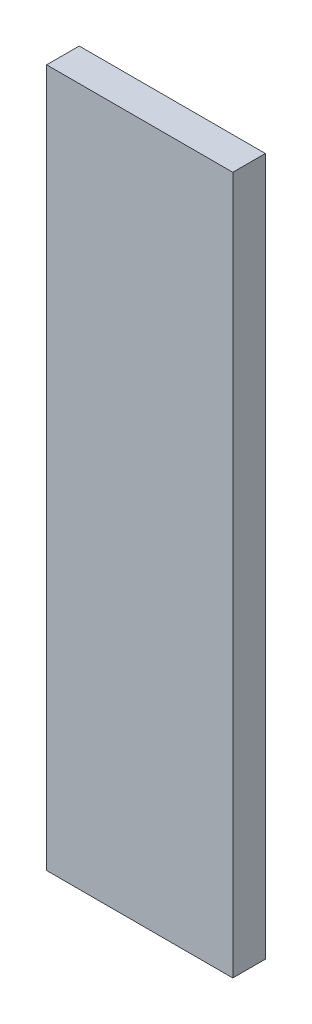
SolidWorks part; units mm, degrees
material "Brass"
ref_plane "Front Plane" through (0, 0, 0) normal (0, 0, 1) x (1, 0, 0)
ref_plane "Top Plane" through (0, 0, 0) normal (0, 1, 0) x (1, 0, 0)
ref_plane "Right Plane" through (0, 0, 0) normal (1, 0, 0) x (0, 0, -1)
sketch "Sketch1" plane through (0, 0, 0) normal (0, 0, 1) x (1, 0, 0)
  line L0 (-18.1394, 68.0022) -> (18.1394, -68.0022) construction
  line L1 (-18.1394, 68.0022) -> (18.1394, 68.0022)
  line L2 (-18.1394, 68.0022) -> (-18.1394, -68.0022)
  line L3 (-18.1394, -68.0022) -> (18.1394, -68.0022)
  line L4 (18.1394, 68.0022) -> (18.1394, -68.0022)
  dimension "D1" = 36.2788
  dimension "D2" = 136.0043
extrude "Extrude1" add sketch "Sketch1" along normal blind 6.35
hole_wizard "#3-48 Tapped Hole1" positions "Sketch2" profile "Sketch3" tap size "#3-48" standard "Ansi Inch"
sketch "Sketch2" plane through (-14.071, -68.0022, 88.9006) normal (0, -1, 0) x (0, 0, -1)
  point P0 (85.7256, 25.8604)
  point P1 (85.7256, 0.8922)
sketch "Sketch3" plane through (11.7894, -68.0022, 3.175) normal (1, 0, 0) x (0, 0, -1)
  line L0 (0, 0) -> (0, 9.743)
  line L1 (0, 9.743) -> (0.9969, 9.144)
  line L2 (0.9969, 9.144) -> (0.997, 7.62)
  line L3 (0.997, 7.62) -> (1.2573, 7.62)
  line L4 (1.2573, 7.62) -> (1.2573, 0)
  line L5 (1.2573, 0) -> (0, 0)
  line L10 (0, 9.743) -> (-0.997, 9.144) construction
  line L11 (0, -6.35) -> (0, 107.95) construction
  dimension "Tap Drill Dia." = 1.9939
  dimension "Tap Drill Depth" = 9.144
  dimension "Thread Major Dia." = 2.5146
  dimension "Drill Angle" = 118
  dimension "Thread Depth Difference" = 1.524
